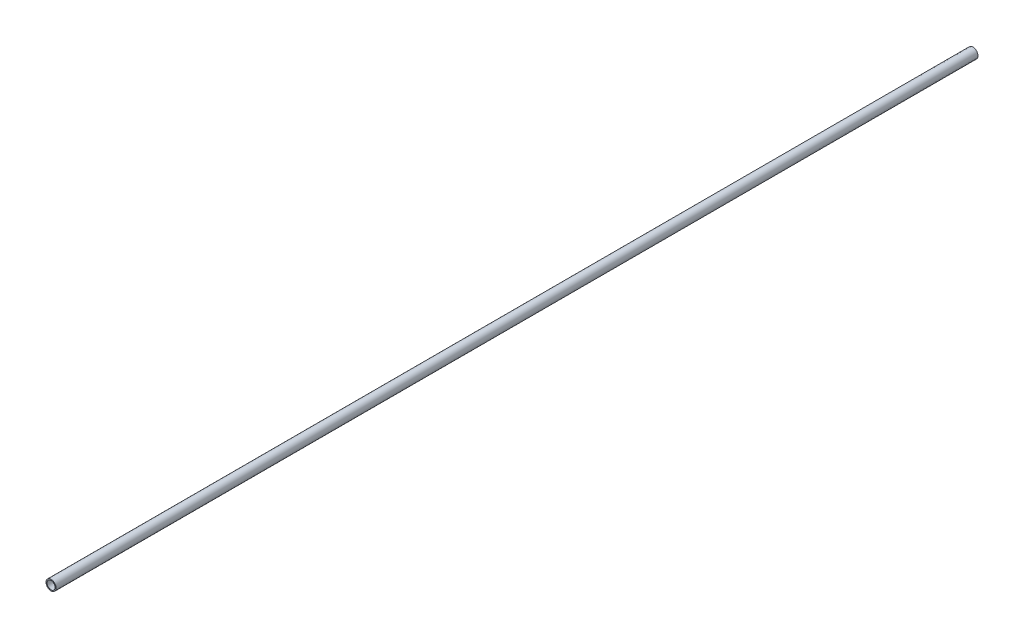
SolidWorks part; units mm, degrees
ref_plane "Front Plane" through (0, 0, 0) normal (0, 0, 1) x (1, 0, 0)
ref_plane "Top Plane" through (0, 0, 0) normal (0, 1, 0) x (1, 0, 0)
ref_plane "Right Plane" through (0, 0, 0) normal (1, 0, 0) x (0, 0, -1)
sketch "Sketch1" plane through (0, 0, 0) normal (0, 0, 1) x (1, 0, 0)
  circle A0 centre (0, 0) radius 16.7005
  dimension "Pipe OD" = 33.401
extrude "Extrude-Thin1" add sketch "Sketch1" along normal mid plane 3048 thin thin type one direction reverse wall 3.3782
